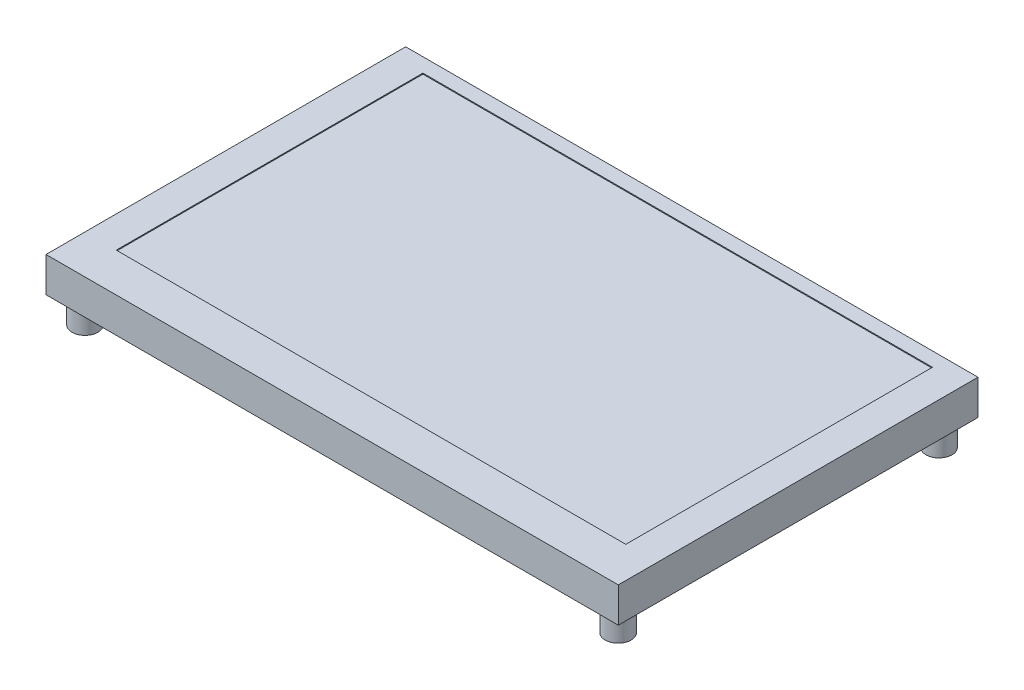
SolidWorks part; units mm, degrees
ref_plane "Front Plane" through (0, 0, 0) normal (0, 0, 1) x (1, 0, 0)
ref_plane "Top Plane" through (0, 0, 0) normal (0, 1, 0) x (1, 0, 0)
ref_plane "Right Plane" through (0, 0, 0) normal (1, 0, 0) x (0, 0, -1)
sketch "Sketch1" plane through (0, 0, 0) normal (0, 1, 0) x (1, 0, 0)
  line L1 (-60.65, -38.12) -> (60.65, -38.12)
  line L2 (-60.65, -38.12) -> (-60.65, 38.12)
  line L3 (-60.65, 38.12) -> (60.65, 38.12)
  line L4 (60.65, -38.12) -> (60.65, 38.12)
  line L5 (-60.65, -38.12) -> (60.65, 38.12) construction
  line L6 (-60.65, 38.12) -> (60.65, -38.12) construction
  point P0 (0, 0)
  dimension "D1" = 121.3
  dimension "D2" = 76.24
extrude "Boss-Extrude1" add sketch "Sketch1" along normal blind 7.4
sketch "Sketch2" plane through (0, 0, 0) normal (0, -1, 0) x (1, 0, 0)
  line L1 (-56.5, -34) -> (56.5, -34) construction
  line L2 (-56.5, -34) -> (-56.5, 34) construction
  line L3 (-56.5, 34) -> (56.5, 34) construction
  line L4 (56.5, -34) -> (56.5, 34) construction
  line L5 (-56.5, -34) -> (56.5, 34) construction
  line L6 (-56.5, 34) -> (56.5, -34) construction
  circle A0 centre (-56.5, 34) radius 2.75
  circle A1 centre (56.5, 34) radius 2.75
  circle A2 centre (56.5, -34) radius 2.75
  circle A3 centre (-56.5, -34) radius 2.75
  circle A4 centre (-56.5, 34) radius 1.5
  circle A5 centre (56.5, 34) radius 1.5
  circle A6 centre (56.5, -34) radius 1.5
  circle A7 centre (-56.5, -34) radius 1.5
  point P0 (0, 0)
  dimension "D3" = 5.5
  dimension "D4" = 3
  dimension "D1" = 113
  dimension "D2" = 68
extrude "Boss-Extrude2" add sketch "Sketch2" along normal blind 5.5
sketch "Sketch3" plane through (0, 0, 0) normal (0, -1, 0) x (1, 0, 0)
  line L0 (60.65, 38.12) -> (60.65, -38.12) construction
  line L1 (-29.35, -24.38) -> (28.65, -24.38) construction
  line L2 (-29.35, -24.38) -> (-29.35, 24.62) construction
  line L3 (-29.35, 24.62) -> (28.65, 24.62) construction
  line L4 (28.65, -24.38) -> (28.65, 24.62) construction
  line L5 (-29.35, -24.38) -> (28.65, 24.62) construction
  line L6 (-29.35, 24.62) -> (28.65, -24.38) construction
  line L7 (-60.65, 38.12) -> (60.65, 38.12) construction
  circle A0 centre (-29.35, 24.62) radius 2.75
  circle A1 centre (-29.35, 24.62) radius 1.5
  circle A2 centre (28.65, 24.62) radius 2.75
  circle A3 centre (28.65, 24.62) radius 1.5
  circle A4 centre (28.65, -24.38) radius 2.75
  circle A5 centre (28.65, -24.38) radius 1.5
  circle A6 centre (-29.35, -24.38) radius 2.75
  circle A7 centre (-29.35, -24.38) radius 1.5
  point P0 (-0.35, 0.12)
  dimension "D3" = 5.5
  dimension "D4" = 3
  dimension "D1" = 58
  dimension "D2" = 49
  dimension "D5" = 32
  dimension "D6" = 13.5
extrude "Boss-Extrude3" add sketch "Sketch3" along normal blind 5.3
sketch "Sketch4" plane through (0, 7.4, 0) normal (0, 1, 0) x (1, 0, 0)
  line L1 (-54, -29.88) -> (54, -29.88)
  line L2 (-54, -29.88) -> (-54, 35.12)
  line L3 (-54, 35.12) -> (54, 35.12)
  line L4 (60.65, -38.12) -> (60.65, 38.12)
  line L5 (60.65, 38.12) -> (-60.65, 38.12)
  line L6 (-60.65, 38.12) -> (-60.65, -38.12)
  line L7 (-60.65, -38.12) -> (60.65, -38.12)
  line L8 (60.65, -38.12) -> (60.65, 38.12)
  line L9 (60.65, 38.12) -> (-60.65, 38.12)
  line L10 (-60.65, 38.12) -> (-60.65, -38.12)
  line L11 (-60.65, -38.12) -> (60.65, -38.12)
  line L12 (54, -29.88) -> (54, 35.12)
  line L13 (-54, -29.88) -> (54, 35.12) construction
  line L14 (-54, 35.12) -> (54, -29.88) construction
  point P2 (0, 2.62)
  dimension "D2" = 108
  dimension "D3" = 65
  dimension "D4" = 3
  dimension "D1" = 0
extrude "Cut-Extrude1" cut sketch "Sketch4" against normal blind 0.2 contours L2 L1 L12 L3
sketch "Sketch5" plane through (0, 0, 0) normal (0, -1, 0) x (-1, 0, 0)
  line L0 (60.65, 38.12) -> (60.65, -38.12) construction
  line L3 (-60.65, 38.12) -> (60.65, 38.12) construction
  circle A0 centre (43.65, 30.12) radius 8
  dimension "D1" = 16
  dimension "D2" = 17
extrude "Boss-Extrude4" add sketch "Sketch5" along normal blind 4
sketch "Sketch6" plane through (0, 0, 0) normal (0, -1, 0) x (1, 0, 0)
  line L0 (-60.65, -38.12) -> (-60.65, 38.12) construction
  line L1 (-47.65, -14.52) -> (-42.65, -14.52)
  line L2 (-47.65, -14.52) -> (-47.65, 7.48)
  line L3 (-47.65, 7.48) -> (-42.65, 7.48)
  line L4 (-42.65, -14.52) -> (-42.65, 7.48)
  line L5 (-47.65, -14.52) -> (-42.65, 7.48) construction
  line L6 (-47.65, 7.48) -> (-42.65, -14.52) construction
  circle A1 centre (-43.65, -30.12) radius 8 construction
  point P0 (-45.15, -3.52)
  dimension "D4" = 15.6
  dimension "D1" = 5
  dimension "D2" = 22
  dimension "D3" = 13
extrude "Boss-Extrude5" add sketch "Sketch6" along normal blind 3
sketch "Sketch8" plane through (0, 7.2, 0) normal (0, 1, 0) x (1, 0, 0)
  line L0 (143.3443, 323.206) -> (948.011, 323.206) construction
